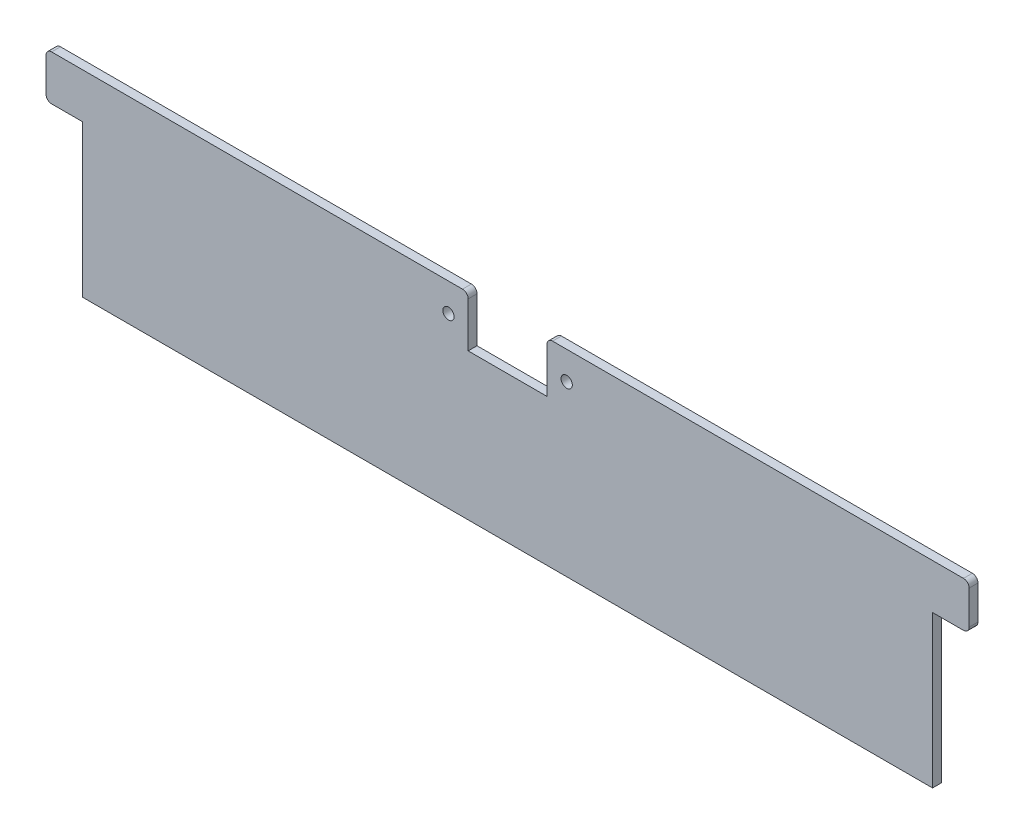
SolidWorks part; units mm, degrees
material "Oak"
ref_plane "Front Plane" through (0, 0, 0) normal (0, 0, 1) x (1, 0, 0)
ref_plane "Top Plane" through (0, 0, 0) normal (0, 1, 0) x (1, 0, 0)
ref_plane "Right Plane" through (0, 0, 0) normal (1, 0, 0) x (0, 0, -1)
sketch "Sketch1" plane through (0, 0, 0) normal (0, 0, 1) x (1, 0, 0)
  line L0 (-260.35, 68.2625) -> (260.35, 68.2625)
  line L1 (260.35, 68.2625) -> (260.35, 42.8625)
  line L2 (260.35, 42.8625) -> (239.7125, 42.8625)
  line L3 (239.7125, 42.8625) -> (239.7125, -42.8625)
  line L4 (239.7125, -42.8625) -> (-239.7125, -42.8625)
  line L5 (-239.7125, -42.8625) -> (-239.7125, 42.8625)
  line L6 (-239.7125, 42.8625) -> (-260.35, 42.8625)
  line L7 (-260.35, 42.8625) -> (-260.35, 68.2625)
  point P3 (0, 68.2625)
  point P12 (-239.7125, 0)
  dimension "D1" = 25.4
  dimension "D2" = 520.7
  dimension "D3" = 479.425
  dimension "D4" = 85.725
extrude "Boss-Extrude1" add sketch "Sketch1" along normal mid plane 5
sketch "Sketch2" plane through (0, 0, 2.5) normal (0, 0, 1) x (1, 0, 0)
  line L0 (260.35, 68.2625) -> (-260.35, 68.2625) construction
  line L1 (-22.225, 39.6875) -> (22.225, 39.6875)
  line L2 (-22.225, 39.6875) -> (-22.225, 68.2625)
  line L3 (-22.225, 68.2625) -> (22.225, 68.2625)
  line L4 (22.225, 39.6875) -> (22.225, 68.2625)
  line L5 (-22.225, 39.6875) -> (22.225, 68.2625) construction
  line L6 (-22.225, 68.2625) -> (22.225, 39.6875) construction
  point P0 (0, 53.975)
  point P7 (0, 0)
  dimension "D1" = 44.45
  dimension "D2" = 28.575
extrude "Cut-Extrude1" cut sketch "Sketch2" against normal through all
fillet "Fillet1" radius 3.175 6 edges at (-260.35, 42.8625, 0) (-260.35, 68.2625, 0) (260.35, 68.2625, 0) (260.35, 42.8625, 0) (22.225, 68.2625, 0) (-22.225, 68.2625, 0)
hole_wizard "1/4 (0.25) Diameter Hole1" positions "Sketch3" profile "Sketch4" hole size "1/4" standard "ANSI Inch" end condition through all
sketch "Sketch3" plane through (0, 0, 2.5) normal (0, 0, 1) x (1, 0, 0)
  line L0 (-33.3375, 52.3875) -> (33.3375, 52.3875) construction
  line L1 (-25.4, 68.2625) -> (-257.175, 68.2625) construction
  point P0 (-33.3375, 52.3875)
  point P2 (33.3375, 52.3875)
  point P9 (0, 52.3875)
  point P13 (0, 0)
  dimension "D1" = 66.675
  dimension "D2" = 15.875
sketch "Sketch4" plane through (-33.3375, 52.3875, 2.5) normal (1, 0, 0) x (0, -1, 0)
  line L0 (0, 0) -> (0, 5)
  line L1 (0, 5) -> (3.175, 5)
  line L2 (3.175, 5) -> (3.175, 0)
  line L5 (3.175, 0) -> (0, 0)
  line L11 (0, -6.35) -> (0, 107.95) construction
  dimension "Thru Hole Dia." = 6.35
  dimension "Thru Hole Depth" = 5
